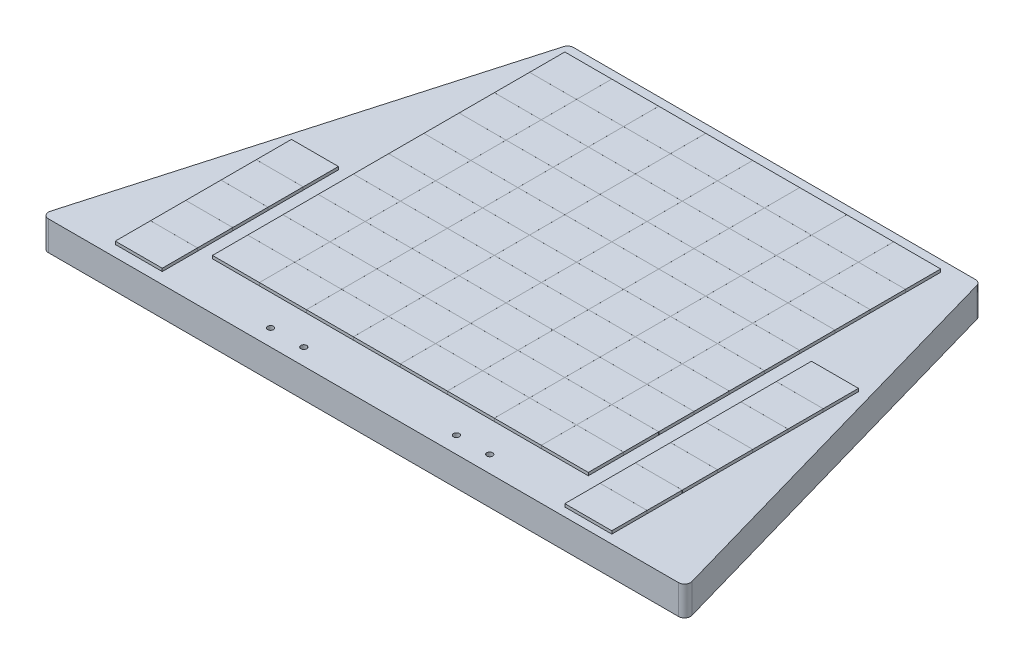
SolidWorks part; units mm, degrees
ref_plane "Front Plane" through (0, 0, 0) normal (0, 0, 1) x (1, 0, 0)
ref_plane "Top Plane" through (0, 0, 0) normal (0, 1, 0) x (1, 0, 0)
ref_plane "Right Plane" through (0, 0, 0) normal (1, 0, 0) x (0, 0, -1)
sketch "Sketch1" plane through (0, 0, 0) normal (0, 1, 0) x (1, 0, 0)
  line L0 (-681.6632, 0) -> (681.6632, 0)
  line L1 (-693.8746, 16.189) -> (-447.1317, 879.789)
  line L2 (-434.9204, 889) -> (434.9204, 889)
  line L3 (447.1317, 879.789) -> (693.8746, 16.189)
  arc A0 (-447.1317, 879.789) -> (-434.9204, 889) centre (-434.9204, 876.3) cw
  arc A1 (434.9204, 889) -> (447.1317, 879.789) centre (434.9204, 876.3) cw
  arc A2 (-681.6632, 0) -> (-693.8746, 16.189) centre (-681.6632, 12.7) cw
  arc A3 (681.6632, 0) -> (693.8746, 16.189) centre (681.6632, 12.7) ccw
  point P7 (-444.5, 889)
  point P10 (444.5, 889)
  point P13 (-698.5, 0)
  point P16 (698.5, 0)
  dimension "D4" = 12.7
  dimension "D5" = 12.7
  dimension "D6" = 12.7
  dimension "D7" = 12.7
  dimension "D1" = 1397
  dimension "D2" = 889
  dimension "D3" = 889
extrude "Boss-Extrude1" add sketch "Sketch1" along normal blind 63.5
sketch "Sketch2" plane through (0, 63.5, 0) normal (0, 1, 0) x (1, 0, 0)
  line L0 (-681.6632, 0) -> (681.6632, 0) construction
  circle A0 centre (-236.982, 35.941) radius 6.35
  circle A1 centre (-165.1, 35.941) radius 6.35
  circle A2 centre (165.1, 35.941) radius 6.35
  circle A3 centre (236.982, 35.941) radius 6.35
  dimension "D1" = 12.7
  dimension "D2" = 12.7
  dimension "D3" = 12.7
  dimension "D4" = 12.7
  dimension "D5" = 71.882
  dimension "D6" = 35.941
  dimension "D7" = 71.882
  dimension "D8" = 35.941
  dimension "D9" = 165.1
  dimension "D10" = 165.1
extrude "Cut-Extrude1" cut sketch "Sketch2" against normal through all
sketch "Sketch3" plane through (0, 63.5, 0) normal (0, 1, 0) x (1, 0, 0)
  line L1 (-429.3727, 864.752) -> (-327.7727, 864.752)
  line L2 (-429.3727, 864.752) -> (-429.3727, 788.552)
  line L3 (-429.3727, 788.552) -> (-327.7727, 788.552)
  line L4 (-327.7727, 864.752) -> (-327.7727, 788.552)
  dimension "D1" = 101.6
  dimension "D2" = 76.2
extrude "Boss-Extrude2" add sketch "Sketch3" along normal blind 6.35
pattern_linear "LPattern1" count 8 spacing 101.6254 along (1, 0, 0) count 10 spacing 76.2254 along (0, 0, 1) of "Boss-Extrude2"
sketch "Sketch4" plane through (0, 63.5, 0) normal (0, 1, 0) x (1, 0, 0)
  line L0 (416.7441, 94.8352) -> (416.7441, 18.6352)
  line L1 (416.7441, 18.6352) -> (518.3441, 18.6352)
  line L2 (518.3441, 18.6352) -> (518.3441, 94.8352)
  line L3 (518.3441, 94.8352) -> (416.7441, 94.8352)
  dimension "D1" = 101.6
  dimension "D2" = 76.2
extrude "Boss-Extrude3" add sketch "Sketch4" along normal blind 6.35
pattern_linear "LPattern2" count 7 spacing 76.2254 along (0, 0, -1) of "Boss-Extrude3"
sketch "Sketch5" plane through (0, 63.5, 0) normal (0, 1, 0) x (1, 0, 0)
  line L0 (-561.2894, 100.448) -> (-459.6894, 100.448)
  line L1 (-459.6894, 100.448) -> (-459.6894, 24.248)
  line L2 (-459.6894, 24.248) -> (-561.2894, 24.248)
  line L3 (-561.2894, 24.248) -> (-554.2556, 34.0702)
  line L4 (-561.2894, 100.448) -> (-561.2894, 24.248)
  dimension "D1" = 76.2
  dimension "D2" = 101.6
extrude "Boss-Extrude4" add sketch "Sketch5" along normal blind 6.35
pattern_linear "LPattern3" count 5 spacing 76.2254 along (0, 0, -1) of "Boss-Extrude4"
